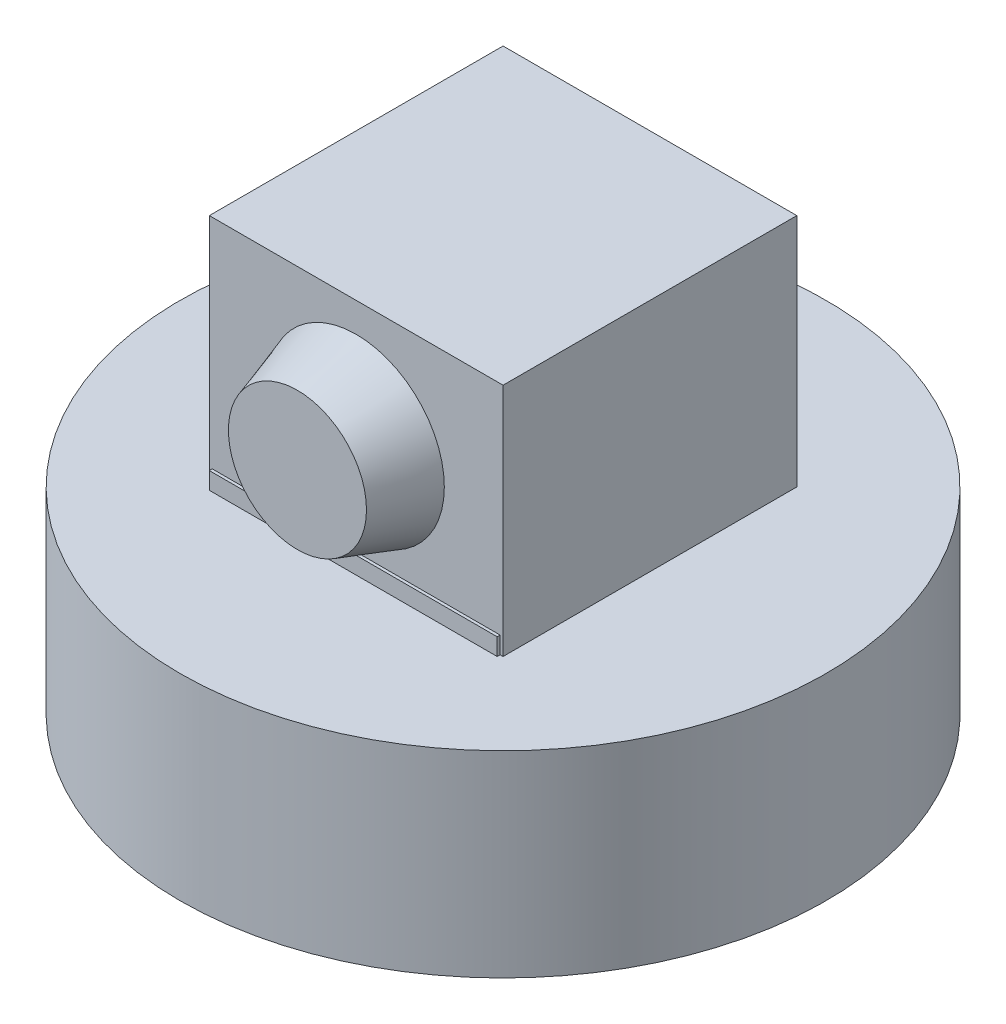
SolidWorks part; units mm, degrees
material "Alloy Steel"
ref_plane "Front Plane" through (0, 0, 0) normal (0, 0, 1) x (1, 0, 0)
ref_plane "Top Plane" through (0, 0, 0) normal (0, 1, 0) x (1, 0, 0)
ref_plane "Right Plane" through (0, 0, 0) normal (1, 0, 0) x (0, 0, -1)
sketch "Sketch1" plane through (0, 0, 0) normal (0, 1, 0) x (1, 0, 0)
  line L0 (-4.5, 8.3098) -> (-4.5, 23.3098)
  line L1 (-4.5, 23.3098) -> (4.5, 23.3098)
  line L2 (4.5, 23.3098) -> (4.5, 8.3098)
  line L3 (-25.4792, 0) -> (23.0325, 0) construction
  line L4 (-4.5, -8.3098) -> (-4.5, -23.3098)
  line L5 (-4.5, -23.3098) -> (4.5, -23.3098)
  line L6 (4.5, -23.3098) -> (4.5, -8.3098)
  arc A0 (-4.5, 8.3098) -> (-4.5, -8.3098) centre (0, 0) ccw
  arc A1 (4.5, -8.3098) -> (4.5, 8.3098) centre (0, 0) ccw
  circle A2 centre (0, 0) radius 110
  dimension "D1" = 18.9
  dimension "D4" = 220
  dimension "D2" = 9
  dimension "D3" = 15
extrude "Boss-Extrude1" add sketch "Sketch1" along normal blind 12
sketch "Sketch2" plane through (0, 12, 0) normal (0, 1, 0) x (1, 0, 0)
  circle A0 centre (0, 0) radius 110
  dimension "D1" = 220
extrude "Boss-Extrude2" add sketch "Sketch2" along normal blind 55
sketch "Sketch3" plane through (0, 67, 0) normal (0, 1, 0) x (1, 0, 0)
  line L0 (0, 130.9769) -> (0, -118.7817) construction
  line L1 (134.9177, 0) -> (-176.6291, 0) construction
  line L3 (-50, 50) -> (50, 50)
  line L4 (-50, 50) -> (-50, -50)
  line L5 (-50, -50) -> (50, -50)
  line L6 (50, 50) -> (50, -50)
  line L7 (-50, 50) -> (50, -50) construction
  line L8 (-50, -50) -> (50, 50) construction
  point P6 (0, 0)
  dimension "D1" = 100
  dimension "D2" = 100
extrude "Boss-Extrude3" add sketch "Sketch3" along normal blind 80
sketch "Sketch4" plane through (0, 0, 50) normal (0, 0, 1) x (1, 0, 0)
  line L0 (-50, 107) -> (50, 107) construction
  line L1 (-50, 147) -> (-50, 67) construction
  line L2 (50, 147) -> (50, 67) construction
  line L3 (0, 147) -> (0, 67) construction
  line L4 (-50, 147) -> (50, 147) construction
  line L5 (110, 67) -> (-110, 67) construction
  circle A0 centre (0, 107) radius 30
  dimension "D1" = 60
extrude "Boss-Extrude4" add sketch "Sketch4" along normal blind 20 draft 18
shell "Shell1" thickness 1
sketch "Sketch6" plane through (0, 0, -49) normal (0, 0, 1) x (1, 0, 0)
  line L0 (49, 147) -> (49, 66) construction
  line L1 (-49, 66) -> (49, 66)
  line L2 (-49, 66) -> (-49, 72.8267)
  line L3 (-49, 72.8267) -> (49, 72.8267)
  line L4 (49, 66) -> (49, 72.8267)
extrude "Boss-Extrude5" add sketch "Sketch6" along normal blind 100
sketch "Sketch7" plane through (0, 0, -49) normal (0, 0, 1) x (1, 0, 0)
  line L1 (-49, 147) -> (49, 147)
  line L2 (-49, 147) -> (-49, 72.8267)
  line L3 (-49, 72.8267) -> (49, 72.8267)
  line L4 (49, 147) -> (49, 72.8267)
extrude "Boss-Extrude6" add sketch "Sketch7" along normal blind 15
sketch "Sketch8" plane through (0, 0, -34) normal (0, 0, 1) x (1, 0, 0)
  line L0 (49, 72.8267) -> (49, 147) construction
  line L1 (-49, 147) -> (49, 147)
  line L2 (-49, 147) -> (-49, 142.0774)
  line L3 (-49, 142.0774) -> (49, 142.0774)
  line L4 (49, 147) -> (49, 142.0774)
extrude "Boss-Extrude7" add sketch "Sketch8" along normal blind 83
